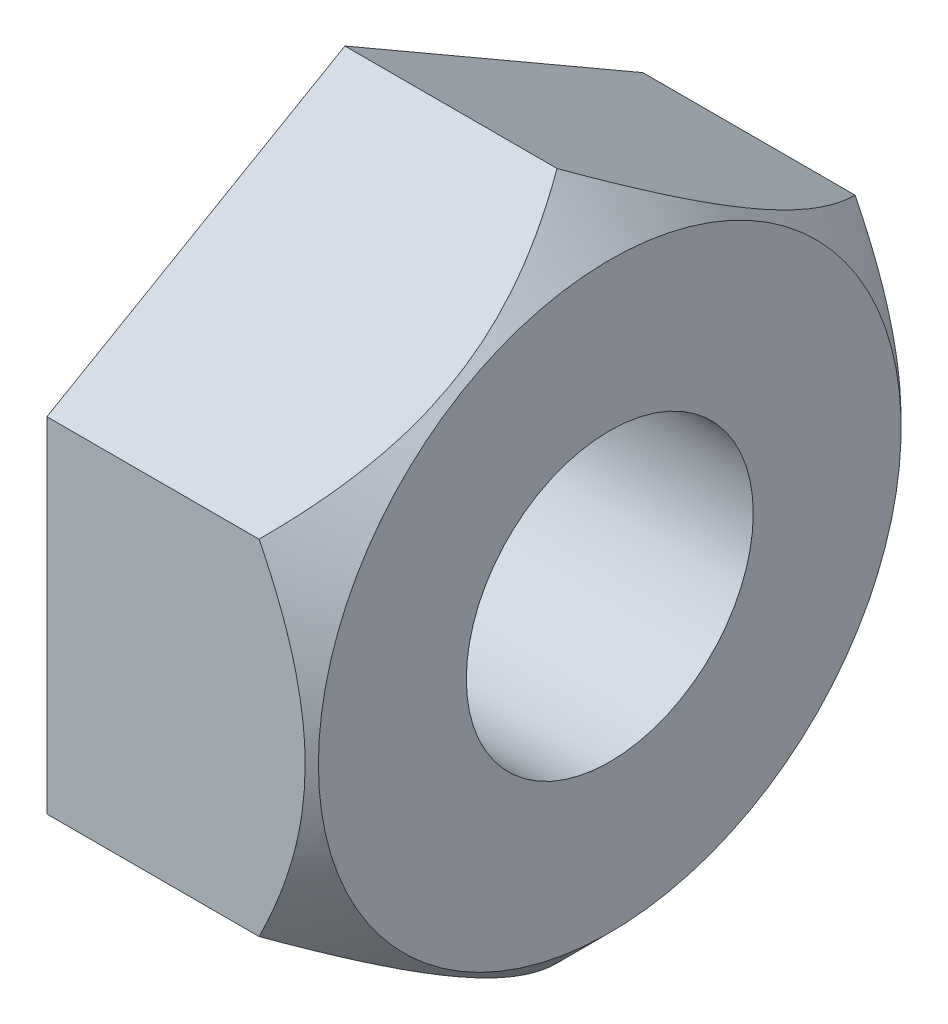
SolidWorks part; units mm, degrees
ref_plane "Front Plane" through (0, 0, 0) normal (0, 0, 1) x (1, 0, 0)
ref_plane "Top Plane" through (0, 0, 0) normal (0, 1, 0) x (1, 0, 0)
ref_plane "Right Plane" through (0, 0, 0) normal (1, 0, 0) x (0, 0, -1)
ref_plane "Plane1" through (0, 0, 0) normal (0, 0, 1) x (1, 0, 0)
sketch "Sketch1" plane through (0, 0, 0) normal (0, 0, 1) x (1, 0, 0)
  line L0 (0, 0) -> (0, 16.2)
  line L1 (0, 16.2) -> (9, 16.2)
  line L2 (9, 16.2) -> (12, 13.2)
  line L3 (12, 13.2) -> (12, 0)
  line L4 (12, 0) -> (0, 0)
  line L5 (12, 0) -> (0, 0) construction
revolve "Revolve1" add sketch "Sketch1" angle 360 about L5
ref_plane "Plane2" through (0, 0, 0) normal (1, 0, 0) x (0, 0, -1)
sketch "Sketch2" plane through (0, 0, 0) normal (1, 0, 0) x (0, 0, -1)
  line L0 (-13.5, -7.7942) -> (0, -15.5885)
  line L1 (0, -15.5885) -> (13.5, -7.7942)
  line L2 (13.5, -7.7942) -> (13.5, 7.7942)
  line L3 (13.5, 7.7942) -> (0, 15.5885)
  line L4 (0, 15.5885) -> (-13.5, 7.7942)
  line L5 (-13.5, 7.7942) -> (-13.5, -7.7942)
  circle A0 centre (0, 0) radius 27
extrude "Cut-Extrude1" cut sketch "Sketch2" along normal blind 12
ref_plane "Plane3" through (0, 0, 0) normal (0, 0, 1) x (1, 0, 0)
sketch "Sketch3" plane through (0, 0, 0) normal (0, 0, 1) x (1, 0, 0)
  line L0 (0, 0) -> (0, 6.5)
  line L1 (0, 6.5) -> (12, 6.5)
  line L2 (12, 6.5) -> (12, 0)
  line L3 (12, 0) -> (0, 0)
  line L4 (12, 0) -> (0, 0) construction
revolve "Cut-Revolve1" cut sketch "Sketch3" angle 360 about L4
cosmetic thread "Cosmetic Thread1" parameters "D1"=12, "D2"=16
